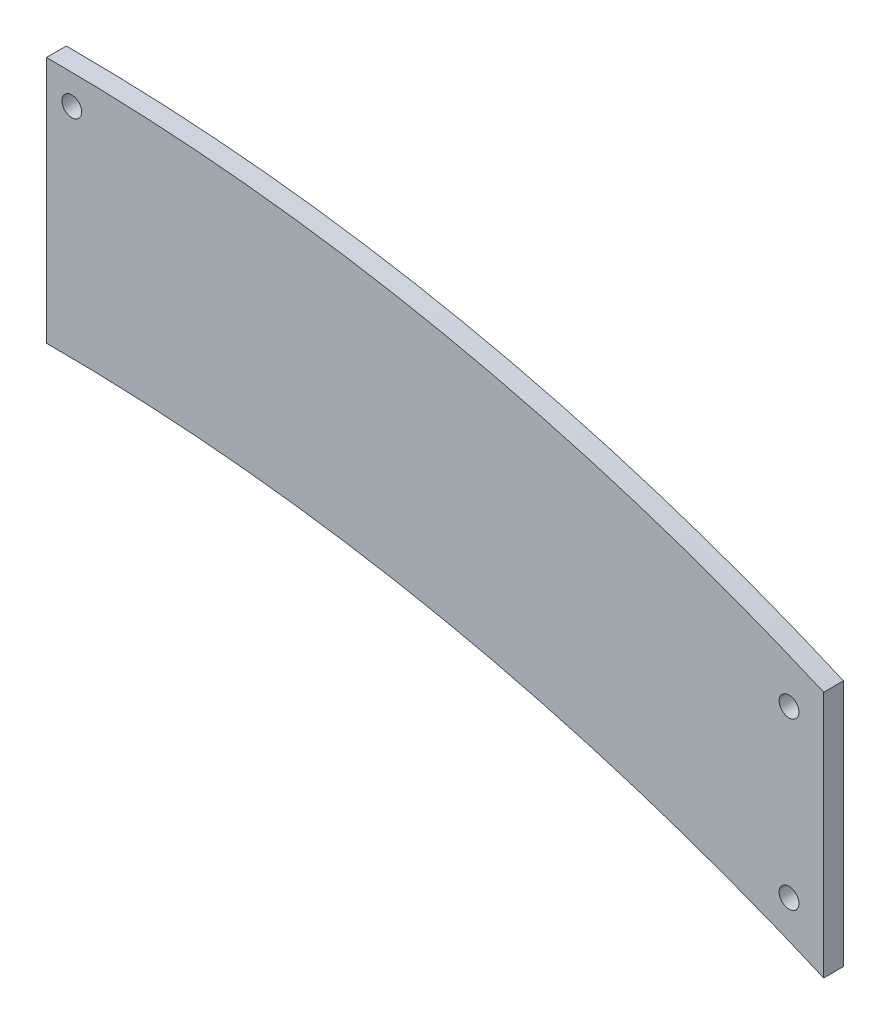
SolidWorks part; units mm, degrees
ref_plane "Front Plane" through (0, 0, 0) normal (0, 0, 1) x (1, 0, 0)
ref_plane "Top Plane" through (0, 0, 0) normal (0, 1, 0) x (1, 0, 0)
ref_plane "Right Plane" through (0, 0, 0) normal (1, 0, 0) x (0, 0, -1)
sketch "Sketch1" plane through (0, 0, 0) normal (0, 0, 1) x (1, 0, 0)
  line L0 (0, 90) -> (0, 0) construction
  line L1 (0, 0) -> (75, 0) construction
  line L3 (0, 40.5106) -> (76.7824, 40.5106) construction
  line L4 (78.5, 24.2339) -> (78.5, -0.7661)
  line L5 (0, 40.5106) -> (0, 15.5106)
  circle A0 centre (2.5552, 37.5106) radius 1
  arc A1 (0, 40.5106) -> (78.5, 24.2339) centre (0, -156.924) cw
  arc A2 (0, 15.5106) -> (78.5, -0.7661) centre (0, -181.924) cw
  circle A3 centre (75, 21.2339) radius 1
  circle A4 centre (75, 4.5) radius 1
  point P22 (2.5552, 37.5106)
  point P23 (75, 21.2339)
  point P25 (75, 4.5)
  dimension "D2" = 40.5106
  dimension "D4" = 197.4346
  dimension "D5" = 2.5552
  dimension "D11" = 2
  dimension "D1" = 25
  dimension "D3" = 78.5
  dimension "D6" = 3
  dimension "D7" = 3.5
  dimension "D8" = 3
  dimension "D9" = 3.5
  dimension "D10" = 5.2661
extrude "Boss-Extrude1" add sketch "Sketch1" along normal blind 2
